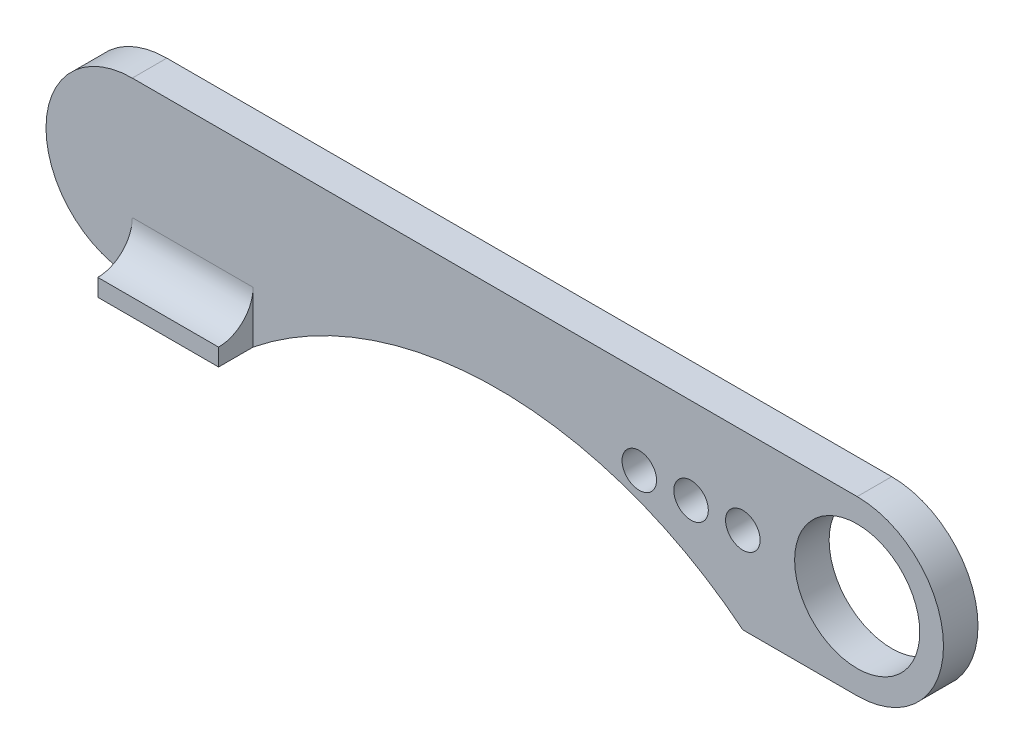
SolidWorks part; units mm, degrees
ref_plane "Front Plane" through (0, 0, 0) normal (0, 0, 1) x (1, 0, 0)
ref_plane "Top Plane" through (0, 0, 0) normal (0, 1, 0) x (1, 0, 0)
ref_plane "Right Plane" through (0, 0, 0) normal (1, 0, 0) x (0, 0, -1)
sketch "Sketch1" plane through (0, 0, 0) normal (0, 0, 1) x (1, 0, 0)
  line L0 (-42, 0) -> (0, 0) construction
  line L1 (-42, 5) -> (0, 5)
  line L2 (-42, -5) -> (0, -5)
  arc A0 (-42, 5) -> (-42, -5) centre (-42, 0) ccw
  arc A1 (0, -5) -> (0, 5) centre (0, 0) ccw
  point P2 (-21, 0)
  dimension "D1" = 42
  dimension "D2" = 10
extrude "Boss-Extrude1" add sketch "Sketch1" along normal blind 2
sketch "Sketch3" plane through (0, 0, 0) normal (0, 0, -1) x (-1, 0, 0)
  line L0 (0, 0) -> (21.8693, 0) construction
  line L1 (3.625, 0) -> (6.625, 0) construction
  line L2 (42, -5) -> (0, -5) construction
  line L3 (35, -5) -> (0, -5)
  line L4 (21.8693, 0) -> (42, 0) construction
  line L6 (9.625, 0) -> (9.625, -5) construction
  line L7 (6.625, 0) -> (6.625, -5) construction
  circle A0 centre (0, 0) radius 3.625
  circle A1 centre (6.625, 0) radius 1
  circle A3 centre (9.625, 0) radius 1
  circle A4 centre (12.625, 0) radius 1
  arc A5 (42, -5) -> (42, 5) centre (42, 0) ccw construction
  arc A6 (42, -5) -> (42, 5) centre (42, 0) ccw
  arc A7 (6.625, -5) -> (35, -5) centre (20.8125, -22.6285) cw
  point P13 (0, 0)
  point P20 (0, 0)
  point P21 (6.7177, -5)
  dimension "D1" = 2
  dimension "D3" = 7.25
  dimension "D2" = 3
  dimension "D4" = 3
  dimension "D5" = 3
  dimension "D6" = 7
extrude "Cut-Extrude1" cut sketch "Sketch3" against normal up to surface (2 mm away) contours A7 L3 | A0 | A1 | A3 | A4 up to face at (-21, 0, 2)
sketch "Sketch4" plane through (0, -5, 0) normal (0, -1, 0) x (1, 0, 0)
  line L0 (-42, 1) -> (-35, 1) construction
  line L8 (-42, 2) -> (-42, 0) construction
  line L9 (-35, 2) -> (-35, 0) construction
  line L11 (-42, 0) -> (-35, 0)
  line L12 (-42, 0) -> (-42, 4)
  line L13 (-42, 4) -> (-35, 4)
  line L14 (-35, 0) -> (-35, 4)
  dimension "D1" = 7
  dimension "D2" = 4
extrude "Boss-Extrude2" add sketch "Sketch4" against normal blind 3
sketch "Sketch7" plane through (-42, 0, 0) normal (-1, 0, 0) x (0, 0, 1)
  circle A0 centre (4, -2) radius 2
extrude "Cut-Extrude2" cut sketch "Sketch7" against normal up to surface (7 mm away) up to face at (-35, -3.5, 3)
